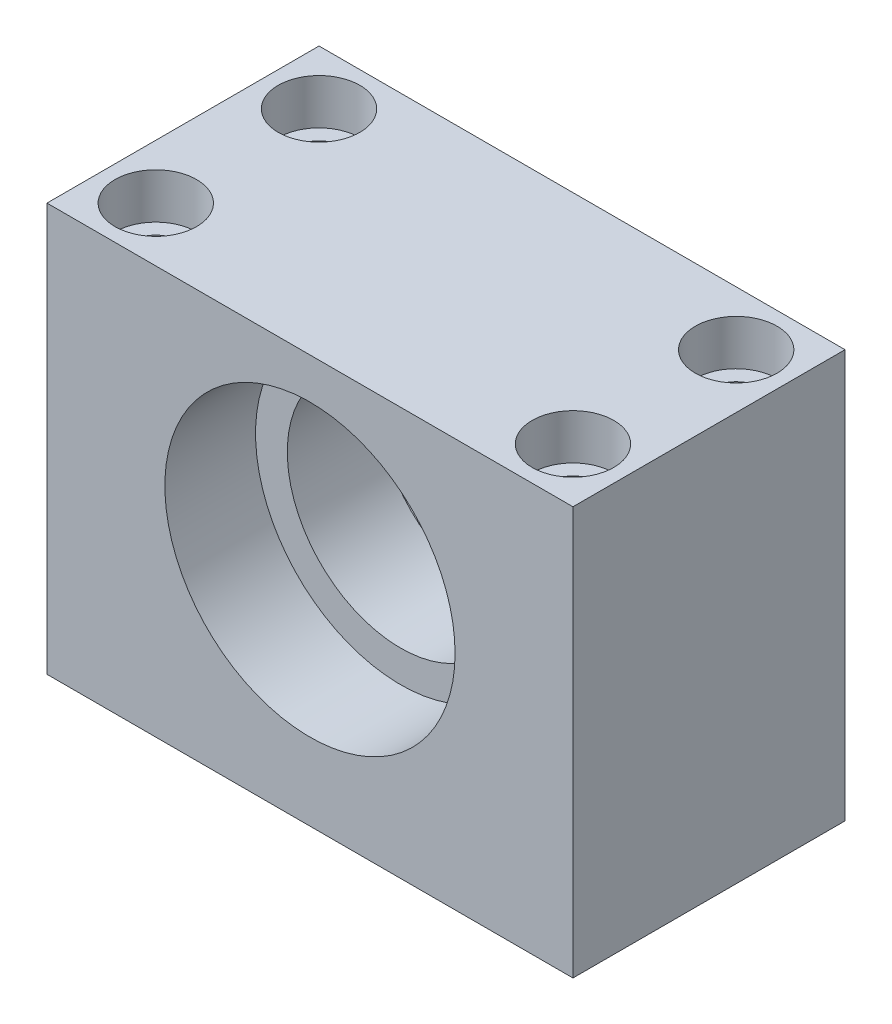
SolidWorks part; units mm, degrees
material "1.0037 (S235JR)"
ref_plane "Płaszczyzna przednia" through (0, 0, 0) normal (0, 0, 1) x (1, 0, 0)
ref_plane "Płaszczyzna górna" through (0, 0, 0) normal (0, 1, 0) x (1, 0, 0)
ref_plane "Płaszczyzna prawa" through (0, 0, 0) normal (1, 0, 0) x (0, 0, -1)
sketch "Szkic1" plane through (0, 0, 0) normal (0, 1, 0) x (1, 0, 0)
  line L1 (-29, -15) -> (29, -15)
  line L2 (-29, -15) -> (-29, 15)
  line L3 (-29, 15) -> (29, 15)
  line L4 (29, -15) -> (29, 15)
  line L5 (-29, -15) -> (29, 15) construction
  line L6 (-29, 15) -> (29, -15) construction
  point P0 (0, 0)
  dimension "D1" = 30
  dimension "D2" = 58
extrude "Dodanie-wyciągnięcie1" add sketch "Szkic1" along normal blind 45
sketch "Szkic3" plane through (0, 0, 15) normal (0, 0, 1) x (1, 0, 0)
  line L0 (0, 45) -> (0, 0) construction
  line L1 (-29, 45) -> (29, 45) construction
  line L2 (-29, 0) -> (29, 0) construction
  circle A0 centre (0, 24.5) radius 12.5
  dimension "D1" = 25
  dimension "D2" = 24.5
extrude "Wytnij-wyciągnięcie2" cut sketch "Szkic3" against normal through all
sketch "Szkic4" plane through (0, 0, 15) normal (0, 0, 1) x (1, 0, 0)
  circle A0 centre (0, 24.5) radius 16
  dimension "D1" = 32
extrude "Wytnij-wyciągnięcie3" cut sketch "Szkic4" against normal blind 10
mirror "Lustro1" about plane through (0, 0, 0) normal (0, 0, 1) of "Wytnij-wyciągnięcie3"
sketch "Szkic5" plane through (0, 45, 0) normal (0, 1, 0) x (1, 0, 0)
  line L8 (23, -9) -> (23, 9)
  line L9 (23, 9) -> (-23, 9)
  line L10 (-23, 9) -> (-23, -9)
  line L11 (-23, -9) -> (23, -9)
  line L12 (23, -9) -> (23, 9)
  line L13 (23, 9) -> (-23, 9)
  line L14 (-23, 9) -> (-23, -9)
  line L15 (-23, -9) -> (23, -9)
  dimension "D1" = 6
hole_wizard "Pogłębienie walcowe pod M5 Wkręt do części metalowych z łbem sześciokątnym1" positions "Szkic9" profile "Szkic6" counterbore size "M5" standard "Ansi Metric" end condition through all
sketch "Szkic9" plane through (0, 45, 0) normal (0, 1, 0) x (1, 0, 0)
  point P0 (-23, -9)
  point P3 (-23, 9)
  point P6 (23, -9)
  point P9 (23, 9)
sketch "Szkic6" plane through (-23, 45, 9) normal (1, 0, 0) x (0, 0, 1)
  line L0 (0, 0) -> (0, 45)
  line L1 (0, 45) -> (2.75, 45)
  line L3 (2.75, 45) -> (2.75, 5)
  line L4 (2.75, 5) -> (4.5, 5)
  line L5 (4.5, 5) -> (4.5, 0)
  line L7 (4.5, 0) -> (0, 0)
  line L11 (0, -6.35) -> (0, 107.95) construction
  dimension "Średnica otworu na wylot" = 5.5
  dimension "Głębokość otworu na wylot" = 45
  dimension "Średnica pogłębienia walcowego" = 9
  dimension "Głębokość pogłębienia walcowego" = 5
